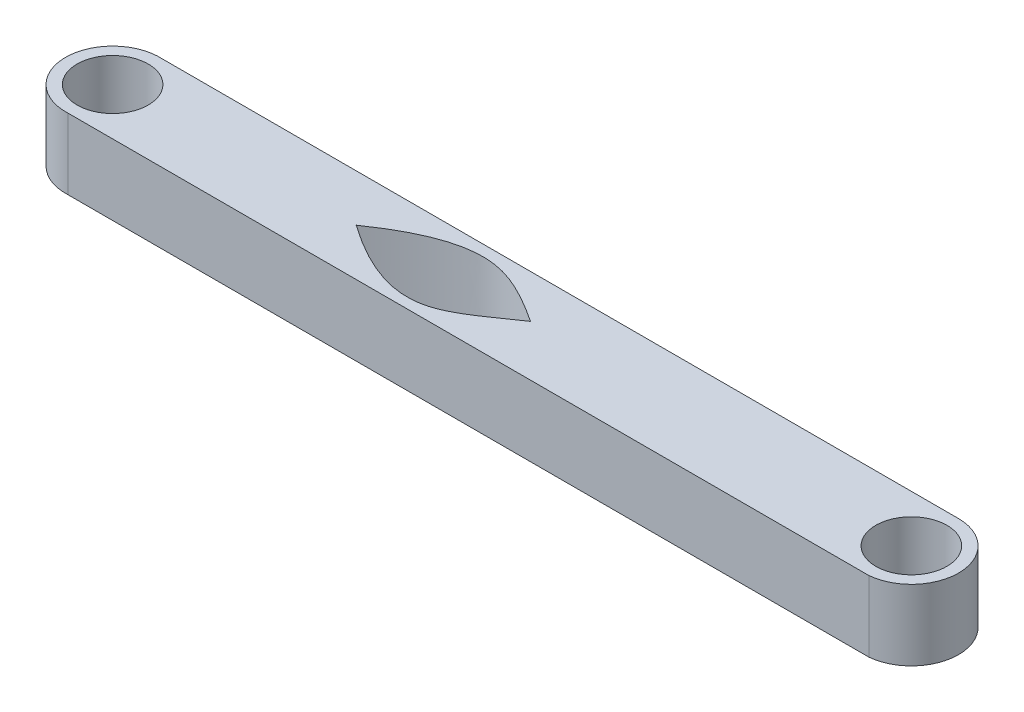
SolidWorks part; units mm, degrees
ref_plane "Alzado" through (0, 0, 0) normal (0, 0, 1) x (1, 0, 0)
ref_plane "Planta" through (0, 0, 0) normal (0, 1, 0) x (1, 0, 0)
ref_plane "Vista lateral" through (0, 0, 0) normal (1, 0, 0) x (0, 0, -1)
sketch "Croquis1" plane through (0, 0, 0) normal (0, 1, 0) x (1, 0, 0)
  line L0 (-61.9588, 0) -> (369.8412, 0)
  line L2 (-64.4776, 50.7365) -> (367.3224, 50.7365)
  arc A0 (-61.9588, 0) -> (-64.4776, 50.7365) centre (-63.2182, 25.3682) cw
  arc A1 (367.3224, 50.7365) -> (369.8412, 0) centre (367.3224, 25.3057) cw
  ellipse E0 centre (-63.2182, 25.3682) end of major axis (89.1818, 25.3682) minor radius 17.6626 (-63.4102, 7.7057) -> (-64.2865, 43.0304) ccw
  dimension "D3" = 152.4
  dimension "D1" = 431.8
  dimension "D2" = 431.8
extrude "Saliente-Extruir1" add sketch "Croquis1" along normal blind 38.1
sketch "Croquis3" plane through (0, 38.1, 0) normal (0, 1, 0) x (1, 0, 0)
  spline S0 degree 3 poles (0, 25.3682) (25.5964, 61.5196) (58.6773, 27.3727) (118.3628, -4.3558) (170.4737, 37.8015) (214.205, 57.3627) (239.3927, 25.3682) knots 0 0 0 0 0.293536 0.509769 0.658148 1 1 1 1
  spline S1 degree 3 poles (0, 25.3682) (25.3352, -11.2056) (59.2665, 24.3168) (147.3333, 68.3318) (200.0919, -25.9182) (239.3927, 25.3682) knots 0 0 0 0 0.293668 0.509999 1 1 1 1
extrude "Cortar-Extruir18" cut sketch "Croquis3" against normal blind 38.1 contours S1 S0
sketch "Croquis4" plane through (0, 38.1, 0) normal (0, 1, 0) x (1, 0, 0)
  line L0 (-64.4776, 50.7365) -> (367.3224, 50.7365) construction
  line L1 (-61.9588, 0) -> (369.8412, 0) construction
  line L2 (-64.4776, 50.7365) -> (367.3224, 50.7365)
  line L3 (-61.9588, 0) -> (369.8412, 0)
  arc A0 (-64.4776, 50.7365) -> (-61.9588, 0) centre (-63.2182, 25.3682) ccw construction
  arc A1 (369.8412, 0) -> (367.3224, 50.7365) centre (367.3224, 25.3057) ccw construction
  arc A2 (-64.4776, 50.7365) -> (-61.9588, 0) centre (-63.2182, 25.3682) ccw
  arc A3 (369.8412, 0) -> (367.3224, 50.7365) centre (367.3224, 25.3057) ccw
  circle A4 centre (-63.2182, 25.3682) radius 19.177
  circle A5 centre (367.3224, 25.3057) radius 19.177
  dimension "D1" = 38.354
  dimension "D2" = 38.354
extrude "Cortar-Extruir21" cut sketch "Croquis4" against normal blind 50.8 flip side to cut
